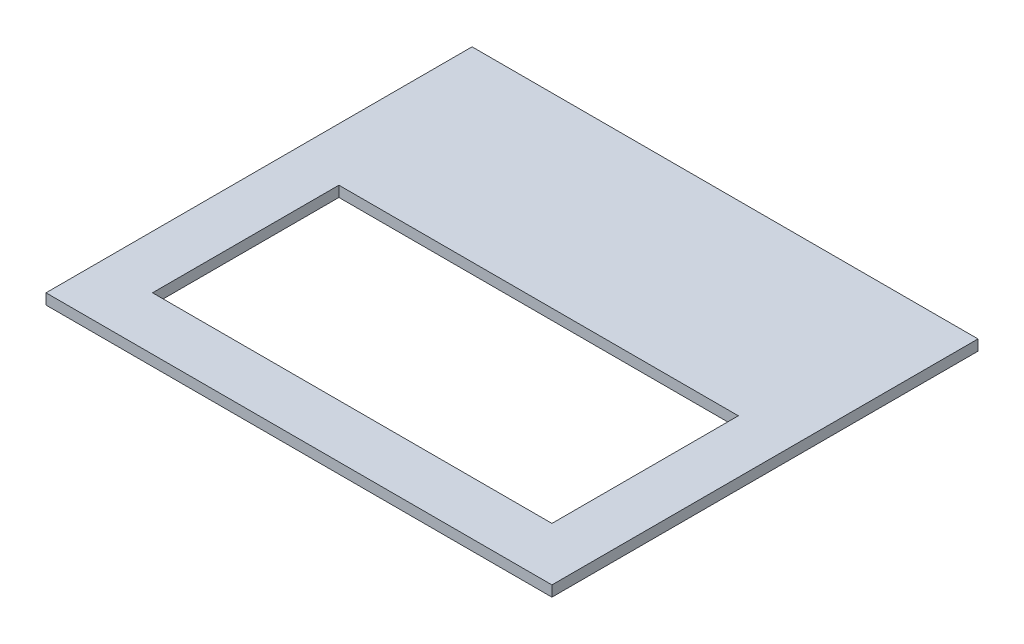
SolidWorks part; units mm, degrees
ref_plane "Front Plane" through (0, 0, 0) normal (0, 0, 1) x (1, 0, 0)
ref_plane "Top Plane" through (0, 0, 0) normal (0, 1, 0) x (1, 0, 0)
ref_plane "Right Plane" through (0, 0, 0) normal (1, 0, 0) x (0, 0, -1)
sketch "Sketch1" plane through (0, 0, 0) normal (0, 1, 0) x (1, 0, 0)
  line L0 (-95, 55) -> (-95, 105)
  line L1 (-75, 35) -> (75, 35)
  line L2 (-75, 35) -> (-75, -35)
  line L3 (-75, -35) -> (75, -35)
  line L4 (75, 35) -> (75, -35)
  line L5 (-75, 35) -> (75, -35) construction
  line L6 (-75, -35) -> (75, 35) construction
  line L7 (95, 55) -> (95, -55)
  line L8 (-95, -55) -> (95, -55)
  line L9 (-95, 55) -> (-95, -55)
  line L10 (-95, 55) -> (95, 55) construction
  line L11 (-95, 105) -> (95, 105)
  line L12 (95, 105) -> (95, 55)
  point P0 (0, 0)
  dimension "D1" = 70
extrude "Boss-Extrude1" add sketch "Sketch1" along normal blind 4
